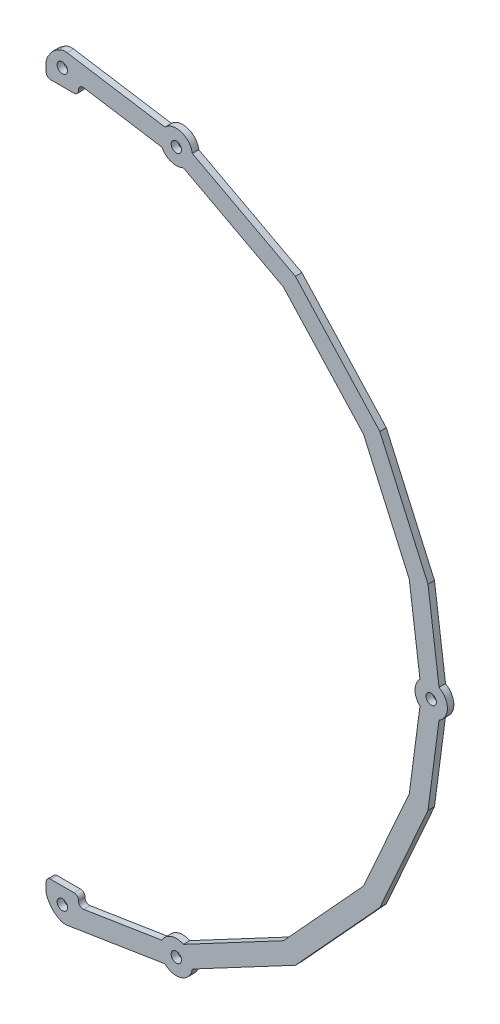
SolidWorks part; units mm, degrees
material "碳纤维板_1600kg_m3"
ref_plane "前视基准面" through (0, 0, 0) normal (0, 0, 1) x (1, 0, 0)
ref_plane "上视基准面" through (0, 0, 0) normal (0, 1, 0) x (1, 0, 0)
ref_plane "右视基准面" through (0, 0, 0) normal (1, 0, 0) x (0, 0, -1)
other "Configuration Table"
sketch "草图1" plane through (0, 0, 0) normal (0, 0, 1) x (1, 0, 0)
  line L0 (0, -115) -> (35.537, -109.3715)
  line L1 (35.537, -109.3715) -> (70.8011, -90.6212)
  line L2 (70.8011, -90.6212) -> (96.4471, -62.6335)
  line L3 (96.4471, -62.6335) -> (111.0815, -29.7642)
  line L4 (111.0815, -29.7642) -> (115, 0)
  line L5 (115, 0) -> (111.0815, 29.7642)
  line L6 (111.0815, 29.7642) -> (96.4471, 62.6335)
  line L7 (96.4471, 62.6335) -> (70.8011, 90.6212)
  line L8 (70.8011, 90.6212) -> (35.537, 109.3715)
  line L9 (35.537, 109.3715) -> (0, 115)
  line L10 (0, 115) -> (0, 111)
  line L11 (0, 111) -> (34.3009, 105.5673)
  line L12 (34.3009, 105.5673) -> (68.3384, 87.4692)
  line L13 (68.3384, 87.4692) -> (93.0924, 60.4549)
  line L14 (93.0924, 60.4549) -> (107.2178, 28.7289)
  line L15 (107.2178, 28.7289) -> (111, 0)
  line L16 (111, 0) -> (107.2178, -28.7289)
  line L17 (107.2178, -28.7289) -> (93.0924, -60.4549)
  line L18 (93.0924, -60.4549) -> (68.3384, -87.4692)
  line L19 (68.3384, -87.4692) -> (34.3009, -105.5673)
  line L20 (34.3009, -105.5673) -> (0, -111)
  line L21 (0, -111) -> (0, -115)
extrude "180度裁切侧框" add sketch "草图1" along normal blind 8
sketch "草图2" plane through (0, 0, 0) normal (0, 0, 1) x (1, 0, 0)
  line L0 (35.585, -103.0471) -> (37.4391, -108.7535)
  line L1 (37.4391, -108.7535) -> (33.6348, -109.9895)
  line L2 (33.6348, -109.9895) -> (31.7807, -104.2832)
  line L3 (31.7807, -104.2832) -> (35.585, -103.0471)
  line L4 (109, 2) -> (115, 2)
  line L5 (115, 2) -> (115, -2)
  line L6 (115, -2) -> (109, -2)
  line L7 (109, -2) -> (109, 2)
  line L8 (31.7807, 104.2832) -> (33.6348, 109.9895)
  line L9 (33.6348, 109.9895) -> (37.4391, 108.7535)
  line L10 (37.4391, 108.7535) -> (35.585, 103.0471)
  line L11 (35.585, 103.0471) -> (31.7807, 104.2832)
extrude "三个侧向支承" add sketch "草图2" along normal blind 36 from offset 8
sketch "草图3" plane through (0, 0, 0) normal (0, 0, 1) x (1, 0, 0)
  line L0 (0, -115) -> (35.537, -109.3715)
  line L1 (35.537, -109.3715) -> (70.8011, -90.6212)
  line L2 (70.8011, -90.6212) -> (96.4471, -62.6335)
  line L3 (96.4471, -62.6335) -> (111.0815, -29.7642)
  line L4 (111.0815, -29.7642) -> (115, 0)
  line L5 (115, 0) -> (111.0815, 29.7642)
  line L6 (111.0815, 29.7642) -> (96.4471, 62.6335)
  line L7 (96.4471, 62.6335) -> (70.8011, 90.6212)
  line L8 (70.8011, 90.6212) -> (35.537, 109.3715)
  line L9 (35.537, 109.3715) -> (0, 115)
  line L10 (0, 115) -> (0, 109)
  line L11 (0, 109) -> (33.6829, 103.6652)
  line L12 (33.6829, 103.6652) -> (67.1071, 85.8932)
  line L13 (67.1071, 85.8932) -> (91.4151, 59.3657)
  line L14 (91.4151, 59.3657) -> (105.2859, 28.2113)
  line L15 (105.2859, 28.2113) -> (109, 0)
  line L16 (109, 0) -> (105.2859, -28.2113)
  line L17 (105.2859, -28.2113) -> (91.4151, -59.3657)
  line L18 (91.4151, -59.3657) -> (67.1071, -85.8932)
  line L19 (67.1071, -85.8932) -> (33.6829, -103.6652)
  line L20 (33.6829, -103.6652) -> (0, -109)
  line L21 (0, -109) -> (0, -115)
extrude "180度裁切上框" add sketch "草图3" along normal blind 3 from offset 44
sketch "草图4" plane through (0, 0, 0) normal (0, 0, 1) x (1, 0, 0)
  circle A0 centre (0, 0) radius 20
  circle A1 centre (0, 0) radius 4
extrude "旧式圆根电机安装座" add sketch "草图4" along normal blind 3 from offset 44 separate body
sketch "草图5" plane through (0, 0, 0) normal (0, 0, 1) x (1, 0, 0)
  line L0 (17, -9) -> (113, -2.5)
  line L1 (113, -2.5) -> (113, 2.5)
  line L2 (113, 2.5) -> (17, 9)
  line L3 (17, 9) -> (17, -9)
extrude "旧式渐窄中梁" add sketch "草图5" along normal blind 3 from offset 44
sketch "草图6" plane through (0, 0, 0) normal (0, 0, 1) x (1, 0, 0)
  line L0 (-5.7367, -8.7347) -> (31.3309, -107.0962)
  line L1 (31.3309, -107.0962) -> (26.6691, -108.9038)
  line L2 (26.6691, -108.9038) -> (-12.2633, -11.2653)
  line L3 (-12.2633, -11.2653) -> (-5.7367, -8.7347)
extrude "旧式直斜侧梁_-1" add sketch "草图6" along normal blind 3 from offset 44
sketch "草图7" plane through (0, 0, 0) normal (0, 0, 1) x (1, 0, 0)
  line L0 (60.2133, 1.2799) -> (91.2349, -66.2401)
  line L1 (91.2349, -66.2401) -> (87.1651, -68.1599)
  line L2 (87.1651, -68.1599) -> (54.7867, -1.2799)
  line L3 (54.7867, -1.2799) -> (60.2133, 1.2799)
extrude "旧式Y形分叉_-1" add sketch "草图7" along normal blind 3 from offset 44
sketch "草图8" plane through (0, 0, 0) normal (0, 0, 1) x (1, 0, 0)
  line L0 (-12.2633, 11.2653) -> (26.6691, 108.9038)
  line L1 (26.6691, 108.9038) -> (31.3309, 107.0962)
  line L2 (31.3309, 107.0962) -> (-5.7367, 8.7347)
  line L3 (-5.7367, 8.7347) -> (-12.2633, 11.2653)
extrude "旧式直斜侧梁_1" add sketch "草图8" along normal blind 3 from offset 44
sketch "草图9" plane through (0, 0, 0) normal (0, 0, 1) x (1, 0, 0)
  line L0 (54.7867, 1.2799) -> (87.1651, 68.1599)
  line L1 (87.1651, 68.1599) -> (91.2349, 66.2401)
  line L2 (91.2349, 66.2401) -> (60.2133, -1.2799)
  line L3 (60.2133, -1.2799) -> (54.7867, 1.2799)
extrude "旧式Y形分叉_1" add sketch "草图9" along normal blind 3 from offset 44
sketch "草图10" plane through (0, 0, 0) normal (0, 0, 1) x (1, 0, 0)
  line L0 (18, -4.5) -> (18, 4.5)
  line L1 (18, 4.5) -> (80.33, 0)
  line L2 (80.33, 0) -> (18, -4.5)
extrude "旧式中梁三角镂空" cut sketch "草图10" along normal blind 3 from offset 44
sketch "草图11" plane through (0, 0, 0) normal (0, 0, 1) x (1, 0, 0)
  circle A0 centre (0, 112) radius 5
  circle A1 centre (0, -112) radius 5
extrude "上连接耳座" add sketch "草图11" along normal blind 3 from offset 44
sketch "草图12" plane through (0, 0, 0) normal (0, 0, 1) x (1, 0, 0)
  line L0 (-5, -107) -> (5, -107)
  line L1 (5, -107) -> (5, -116.2081)
  line L2 (5, -116.2081) -> (0, -117)
  line L3 (0, -117) -> (-3, -115)
  line L4 (-3, -115) -> (-5, -112)
  line L5 (-5, -112) -> (-5, -107)
  line L6 (-5, 107) -> (5, 107)
  line L7 (5, 107) -> (5, 116.2081)
  line L8 (5, 116.2081) -> (0, 117)
  line L9 (0, 117) -> (-3, 115)
  line L10 (-3, 115) -> (-5, 112)
  line L11 (-5, 112) -> (-5, 107)
extrude "下连接耳座" add sketch "草图12" along normal blind 8
sketch "草图13" plane through (0, 0, 0) normal (0, 0, 1) x (1, 0, 0)
  circle A0 centre (13.435, 0) radius 1.6
  circle A1 centre (-13.435, 0) radius 1.6
  circle A2 centre (0, 13.435) radius 1.6
  circle A3 centre (0, -13.435) radius 1.6
  circle A4 centre (0, 112) radius 1.6
  circle A5 centre (0, -112) radius 1.6
extrude "电机及上连接孔" cut sketch "草图13" along normal blind 3 from offset 44
sketch "草图14" plane through (0, 0, 0) normal (0, 0, 1) x (1, 0, 0)
  circle A0 centre (0, 112) radius 1.6
  circle A1 centre (0, -112) radius 1.6
extrude "下连接孔" cut sketch "草图14" along normal blind 8
sketch "草图15" plane through (0, 0, 0) normal (0, 0, 1) x (1, 0, 0)
  line L0 (-300, -300) -> (300, -300)
  line L1 (300, -300) -> (300, 300)
  line L2 (300, 300) -> (-300, 300)
  line L3 (-300, 300) -> (-300, -300)
extrude "上下拆分_仅保留下层" cut sketch "草图15" along normal blind 60 from offset 8
sketch "草图16" plane through (0, 0, 0) normal (0, 0, 1) x (1, 0, 0)
  line L0 (0, -117) -> (36.155, -111.2736)
  line L1 (36.155, -111.2736) -> (72.0324, -92.1973)
  line L2 (72.0324, -92.1973) -> (98.1245, -63.7228)
  line L3 (98.1245, -63.7228) -> (113.0133, -30.2818)
  line L4 (113.0133, -30.2818) -> (117, 0)
  line L5 (117, 0) -> (113.0133, 30.2818)
  line L6 (113.0133, 30.2818) -> (98.1245, 63.7228)
  line L7 (98.1245, 63.7228) -> (72.0324, 92.1973)
  line L8 (72.0324, 92.1973) -> (36.155, 111.2736)
  line L9 (36.155, 111.2736) -> (0, 117)
  line L10 (0, 117) -> (0, 114)
  line L11 (0, 114) -> (35.2279, 108.4204)
  line L12 (35.2279, 108.4204) -> (70.1854, 89.8332)
  line L13 (70.1854, 89.8332) -> (95.6084, 62.0888)
  line L14 (95.6084, 62.0888) -> (110.1155, 29.5054)
  line L15 (110.1155, 29.5054) -> (114, 0)
  line L16 (114, 0) -> (110.1155, -29.5054)
  line L17 (110.1155, -29.5054) -> (95.6084, -62.0888)
  line L18 (95.6084, -62.0888) -> (70.1854, -89.8332)
  line L19 (70.1854, -89.8332) -> (35.2279, -108.4204)
  line L20 (35.2279, -108.4204) -> (0, -114)
  line L21 (0, -114) -> (0, -117)
extrude "外圈径向加厚2mm" add sketch "草图16" along normal blind 8
sketch "草图17" plane through (0, 0, 0) normal (0, 0, 1) x (1, 0, 0)
  circle A0 centre (35.2279, -108.4204) radius 5
extrude "M3铝柱下定位耳" add sketch "草图17" along normal blind 8
sketch "草图18" plane through (0, 0, 0) normal (0, 0, 1) x (1, 0, 0)
  circle A0 centre (114, 0) radius 5
extrude "凸台-拉伸3" add sketch "草图18" along normal blind 8
sketch "草图19" plane through (0, 0, 0) normal (0, 0, 1) x (1, 0, 0)
  circle A0 centre (35.2279, 108.4204) radius 5
extrude "凸台-拉伸4" add sketch "草图19" along normal blind 8
sketch "草图20" plane through (0, 0, 0) normal (0, 0, 1) x (1, 0, 0)
  circle A0 centre (35.2279, -108.4204) radius 1.6
  circle A1 centre (114, 0) radius 1.6
  circle A2 centre (35.2279, 108.4204) radius 1.6
extrude "三处M3下层固定孔" cut sketch "草图20" along normal blind 8
sketch "草图21" plane through (0, 0, 0) normal (0, 0, 1) x (1, 0, 0)
  circle A0 centre (35.2279, -108.4204) radius 3.1
  circle A1 centre (114, 0) radius 3.1
  circle A2 centre (35.2279, 108.4204) radius 3.1
extrude "40mm铝柱沉座_深4mm_D6p2" cut sketch "草图21" along normal blind 4 from offset 4
fillet "下端耳外缘圆角_R3p9_轮廓内收" radius 3.9 6 edges at (0, 117, 4) (-3, 115, 4) (-5, 112, 4) (0, -117, 4) (-3, -115, 4) (-5, -112, 4)
sketch "草图22" plane through (0, 0, 0) normal (0, 0, 1) x (1, 0, 0)
  line L0 (-300, -300) -> (300, -300)
  line L1 (300, -300) -> (300, 300)
  line L2 (300, 300) -> (-300, 300)
  line L3 (-300, 300) -> (-300, -300)
extrude "统一2mm板厚_下层保留0至2" cut sketch "草图22" along normal blind 8 from offset 2
fillet "圆角4" radius 1.4 6 edges at (-5, 107, 1) (5, 107, 1) (5, 110.2081, 1) (5, -110.2081, 1) (-5, -107, 1) (5, -107, 1)
